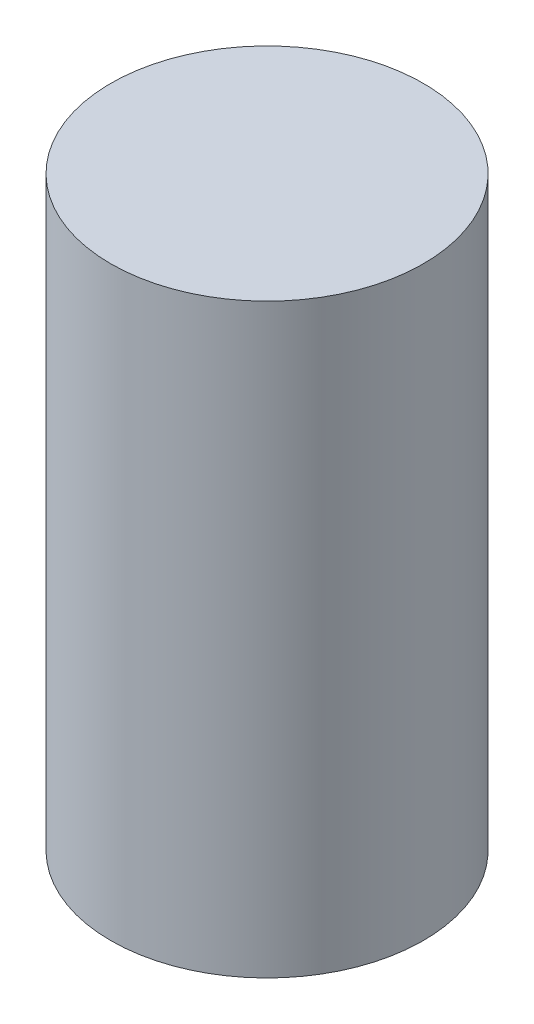
SolidWorks part; units mm, degrees
ref_plane "Front Plane" through (0, 0, 0) normal (0, 0, 1) x (1, 0, 0)
ref_plane "Top Plane" through (0, 0, 0) normal (0, 1, 0) x (1, 0, 0)
ref_plane "Right Plane" through (0, 0, 0) normal (1, 0, 0) x (0, 0, -1)
sketch "Sketch1" plane through (0, 0, 0) normal (0, 1, 0) x (1, 0, 0)
  circle A0 centre (0, 0) radius 4
  dimension "D1" = 8
extrude "Boss-Extrude1" add sketch "Sketch1" along normal blind 15
